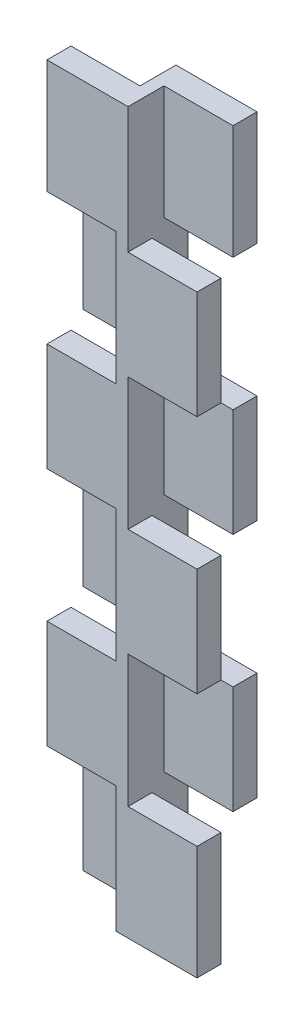
SolidWorks part; units mm, degrees
ref_plane "Front Plane" through (0, 0, 0) normal (0, 0, 1) x (1, 0, 0)
ref_plane "Top Plane" through (0, 0, 0) normal (0, 1, 0) x (1, 0, 0)
ref_plane "Right Plane" through (0, 0, 0) normal (1, 0, 0) x (0, 0, -1)
sketch "Sketch1" plane through (0, 0, 0) normal (0, 0, 1) x (1, 0, 0)
  line L1 (0, 0) -> (0.25, 0)
  line L2 (0, 0) -> (0, 1.2)
  line L3 (0, 1.2) -> (0.25, 1.2)
  line L4 (0.25, 0) -> (0.25, 1.2)
  dimension "D1" = 0.25
  dimension "D2" = 1.2
extrude "Boss-Extrude1" add sketch "Sketch1" along normal blind 0.1 contours L2 L3 L4 L1
sketch "Sketch2" plane through (0.25, 0, 0) normal (1, 0, 0) x (0, 0, -1)
  line L0 (-0.05, 1.2) -> (-0.05, 0) construction
  line L1 (-0.1, 1.2) -> (0, 1.2) construction
  line L2 (-0.1, 0) -> (0, 0) construction
  line L3 (-0.06, 1.2) -> (-0.06, 0) construction
  line L4 (-0.04, 0) -> (-0.04, 1.2) construction
  line L5 (-0.1, 0.6) -> (0, 0.6) construction
  line L6 (-0.1, 0) -> (-0.1, 1.2) construction
  line L7 (0, 0) -> (0, 1.2) construction
  line L8 (-0.1, 0.61) -> (0, 0.61) construction
  line L9 (-0.1, 0.59) -> (0, 0.59) construction
  line L10 (-0.1, 0.4) -> (0, 0.4) construction
  line L11 (-0.1, 0.41) -> (0, 0.41) construction
  line L12 (-0.1, 0.39) -> (0, 0.39) construction
  line L13 (-0.1, 0.8) -> (0, 0.8) construction
  line L14 (-0.1, 0.81) -> (0, 0.81) construction
  line L15 (-0.1, 1) -> (0, 1) construction
  line L16 (0, 1.01) -> (-0.1, 1.01) construction
  line L17 (-0.1, 0.99) -> (0, 0.99) construction
  line L18 (0, 0.79) -> (-0.1, 0.79) construction
  line L19 (-0.1, 0.2) -> (0, 0.2) construction
  line L20 (0, 0.21) -> (-0.1, 0.21) construction
  line L21 (0, 0.19) -> (-0.1, 0.19) construction
  line L22 (-0.04, 1.2) -> (-0.1, 1.2)
  line L23 (-0.1, 1.2) -> (-0.1, 0.99)
  line L24 (-0.1, 0.99) -> (-0.06, 0.99)
  line L25 (-0.06, 0.99) -> (-0.06, 0.81)
  line L26 (-0.06, 0.81) -> (-0.1, 0.81)
  line L27 (-0.1, 0.81) -> (-0.1, 0.59)
  line L28 (-0.1, 0.59) -> (-0.06, 0.59)
  line L29 (-0.06, 0.59) -> (-0.06, 0.41)
  line L30 (-0.06, 0.41) -> (-0.1, 0.41)
  line L31 (-0.1, 0.41) -> (-0.1, 0.19)
  line L32 (-0.1, 0.19) -> (-0.06, 0.19)
  line L33 (-0.06, 0.19) -> (-0.06, 0)
  line L34 (-0.06, 0) -> (0, 0)
  line L35 (0, 0) -> (0, 0.21)
  line L36 (0, 0.21) -> (-0.04, 0.21)
  line L37 (-0.04, 0.21) -> (-0.04, 0.39)
  line L38 (-0.04, 0.39) -> (0, 0.39)
  line L39 (0, 0.39) -> (0, 0.61)
  line L40 (0, 0.61) -> (-0.04, 0.61)
  line L41 (-0.04, 0.61) -> (-0.04, 0.79)
  line L42 (-0.04, 0.79) -> (0, 0.79)
  line L43 (0, 0.79) -> (0, 1.01)
  line L44 (0, 1.01) -> (-0.04, 1.01)
  line L45 (-0.04, 1.01) -> (-0.04, 1.2)
  dimension "D1" = 0.01
  dimension "D2" = 0.01
  dimension "D3" = 0.01
  dimension "D4" = 0.01
  dimension "D5" = 0.01
  dimension "D6" = 0.01
  dimension "D7" = 0.01
  dimension "D8" = 0.01
  dimension "D9" = 0.01
  dimension "D10" = 0.01
  dimension "D11" = 0.01
  dimension "D12" = 0.01
  dimension "D13" = 0.2
  dimension "D14" = 0.2
  dimension "D15" = 0.2
  dimension "D16" = 0.2
extrude "Cut-Extrude1" cut sketch "Sketch2" against normal blind 0.115
sketch "Sketch3" plane through (0, 0, 0) normal (-1, 0, 0) x (0, 0, 1)
  line L0 (0.05, 1.2) -> (0.05, 0) construction
  line L1 (0.1, 1.2) -> (0, 1.2) construction
  line L2 (0.1, 0) -> (0, 0) construction
  line L3 (0.06, 1.2) -> (0.06, 0) construction
  line L4 (0.04, 1.2) -> (0.04, 0) construction
  line L5 (0, 0.6) -> (0.1, 0.6) construction
  line L6 (0, 0) -> (0, 1.2) construction
  line L7 (0.1, 0) -> (0.1, 1.2) construction
  line L8 (0, 0.61) -> (0.1, 0.61) construction
  line L9 (0, 0.59) -> (0.1, 0.59) construction
  line L10 (0, 0.79) -> (0.1, 0.79) construction
  line L11 (0, 0.8) -> (0.1, 0.8) construction
  line L12 (0, 0.81) -> (0.1, 0.81) construction
  line L13 (0, 1.01) -> (0.1, 1.01) construction
  line L14 (0, 1) -> (0.1, 1) construction
  line L15 (0, 0.99) -> (0.1, 0.99) construction
  line L16 (0, 0.4) -> (0.1, 0.4) construction
  line L17 (0, 0.41) -> (0.1, 0.41) construction
  line L18 (0, 0.39) -> (0.1, 0.39) construction
  line L19 (0, 0.2) -> (0.1, 0.2) construction
  line L20 (0, 0.21) -> (0.1, 0.21) construction
  line L21 (0, 0.19) -> (0.1, 0.19) construction
  line L22 (0.06, 1.01) -> (0.06, 1.2)
  line L23 (0.06, 1.2) -> (0, 1.2)
  line L24 (0, 1.2) -> (0, 0.99)
  line L25 (0, 0.99) -> (0.04, 0.99)
  line L26 (0.04, 0.99) -> (0.04, 0.81)
  line L27 (0.04, 0.81) -> (0, 0.81)
  line L28 (0, 0.81) -> (0, 0.59)
  line L29 (0, 0.59) -> (0.04, 0.59)
  line L30 (0.04, 0.59) -> (0.04, 0.41)
  line L31 (0.04, 0.41) -> (0, 0.41)
  line L32 (0, 0.41) -> (0, 0.19)
  line L33 (0, 0.19) -> (0.04, 0.19)
  line L34 (0.04, 0.19) -> (0.04, 0)
  line L35 (0.04, 0) -> (0.1, 0)
  line L36 (0.1, 0) -> (0.1, 0.21)
  line L37 (0.1, 0.21) -> (0.06, 0.21)
  line L38 (0.06, 0.21) -> (0.06, 0.39)
  line L39 (0.06, 0.39) -> (0.1, 0.39)
  line L40 (0.1, 0.39) -> (0.1, 0.61)
  line L41 (0.1, 0.61) -> (0.06, 0.61)
  line L42 (0.06, 0.61) -> (0.06, 0.79)
  line L43 (0.06, 0.79) -> (0.1, 0.79)
  line L44 (0.1, 0.79) -> (0.1, 1.01)
  line L45 (0.1, 1.01) -> (0.06, 1.01)
  dimension "D1" = 0.01
  dimension "D2" = 0.01
  dimension "D3" = 0.01
  dimension "D4" = 0.01
  dimension "D5" = 0.01
  dimension "D6" = 0.01
  dimension "D8" = 0.01
  dimension "D9" = 0.01
  dimension "D11" = 0.01
  dimension "D12" = 0.01
  dimension "D13" = 0.2
  dimension "D16" = 0.2
  dimension "D7" = 0.2
  dimension "D10" = 0.2
  dimension "D14" = 0.01
  dimension "D15" = 0.01
extrude "Cut-Extrude2" cut sketch "Sketch3" against normal blind 0.115
equation "\"t\"= 0.25'thickness of the sheets"
equation "\"t_cf\" = 0.115'thickness of single carbon fiber layer"
equation "\"t_kapton\" = 0.025'thickness of single Kapton flex layer"
equation "\"t_fr4\" = 0.1'thickness of FR4 with copper layer"
equation "\"joint_flex\"= 0.1'Width of flextures gap"
equation "\"joint_flex_eff\"= 0.02'Width of flecture after castelation"
equation "\"joint_fold\"= 0.2'Width of folding joints for 90deg fold"
equation "\"gap_tolerance\"= 0.002'Width to have interfecence fit between carbon fiber inserts"
equation "\"assemble_angle\"= 90'Angle of assembly parts"
equation "\"link_lift\"= 0.5'Actuation linkage amplification for the lift motion"
equation "\"link_swing\"= 0.45'Actuation linkage amplification for the swing motion"
equation "\"D1@Sketch1\"=\"t\""
equation "\"D1@Boss-Extrude1\"=\"joint_flex\""
equation "\"D1@Sketch2\"=\"joint_flex_eff\"/2"
equation "\"D2@Sketch2\"=\"joint_flex_eff\"/2"
equation "\"fold_gap\"= 0.01"
equation "\"D3@Sketch2\"=\"fold_gap\""
equation "\"D4@Sketch2\"=\"fold_gap\""
equation "\"D5@Sketch2\"=\"fold_gap\""
equation "\"D6@Sketch2\"=\"fold_gap\""
equation "\"D7@Sketch2\"=\"fold_gap\""
equation "\"D8@Sketch2\"=\"fold_gap\""
equation "\"D9@Sketch2\"=\"fold_gap\""
equation "\"D10@Sketch2\"=\"fold_gap\""
equation "\"D11@Sketch2\"=\"fold_gap\""
equation "\"D12@Sketch2\"=\"fold_gap\""
equation "\"D1@Cut-Extrude1\"=\"t_cf\""
equation "\"D1@Sketch3\"=\"joint_flex_eff\"/2"
equation "\"D2@Sketch3\"=\"joint_flex_eff\"/2"
equation "\"D3@Sketch3\"=\"fold_gap\""
equation "\"D4@Sketch3\"=\"fold_gap\""
equation "\"D5@Sketch3\"=\"fold_gap\""
equation "\"D6@Sketch3\"=\"fold_gap\""
equation "\"D8@Sketch3\"=\"fold_gap\""
equation "\"D9@Sketch3\"=\"fold_gap\""
equation "\"D11@Sketch3\"=\"fold_gap\""
equation "\"D12@Sketch3\"=\"fold_gap\""
equation "\"D14@Sketch3\"=\"fold_gap\""
equation "\"D15@Sketch3\"=\"fold_gap\""
equation "\"D1@Cut-Extrude2\"=\"t_cf\""
